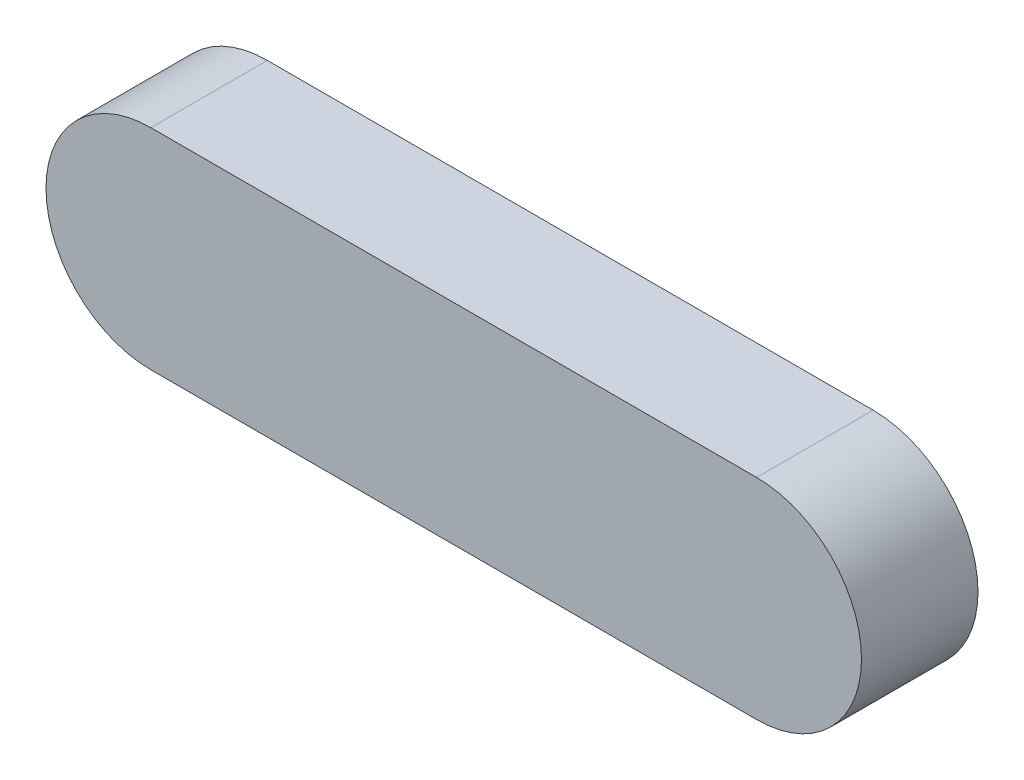
SolidWorks part; units mm, degrees
material "普通碳钢"
ref_plane "前视基准面" through (0, 0, 0) normal (0, 0, 1) x (1, 0, 0)
ref_plane "上视基准面" through (0, 0, 0) normal (0, 1, 0) x (1, 0, 0)
ref_plane "右视基准面" through (0, 0, 0) normal (1, 0, 0) x (0, 0, -1)
sketch "草图1" plane through (0, 0, 0) normal (0, 0, 1) x (1, 0, 0)
  line L0 (0, -27.4898) -> (0, 37.418) construction
  line L1 (-52, 18) -> (52, 18)
  line L3 (-52, -18) -> (52, -18)
  arc A0 (-52, 18) -> (-52, -18) centre (-52, 0) ccw
  arc A1 (52, 18) -> (52, -18) centre (52, 0) cw
  dimension "D1" = 104
  dimension "D3" = 36
  dimension "D4" = 18
extrude "拉伸1" add sketch "草图1" along normal blind 20
